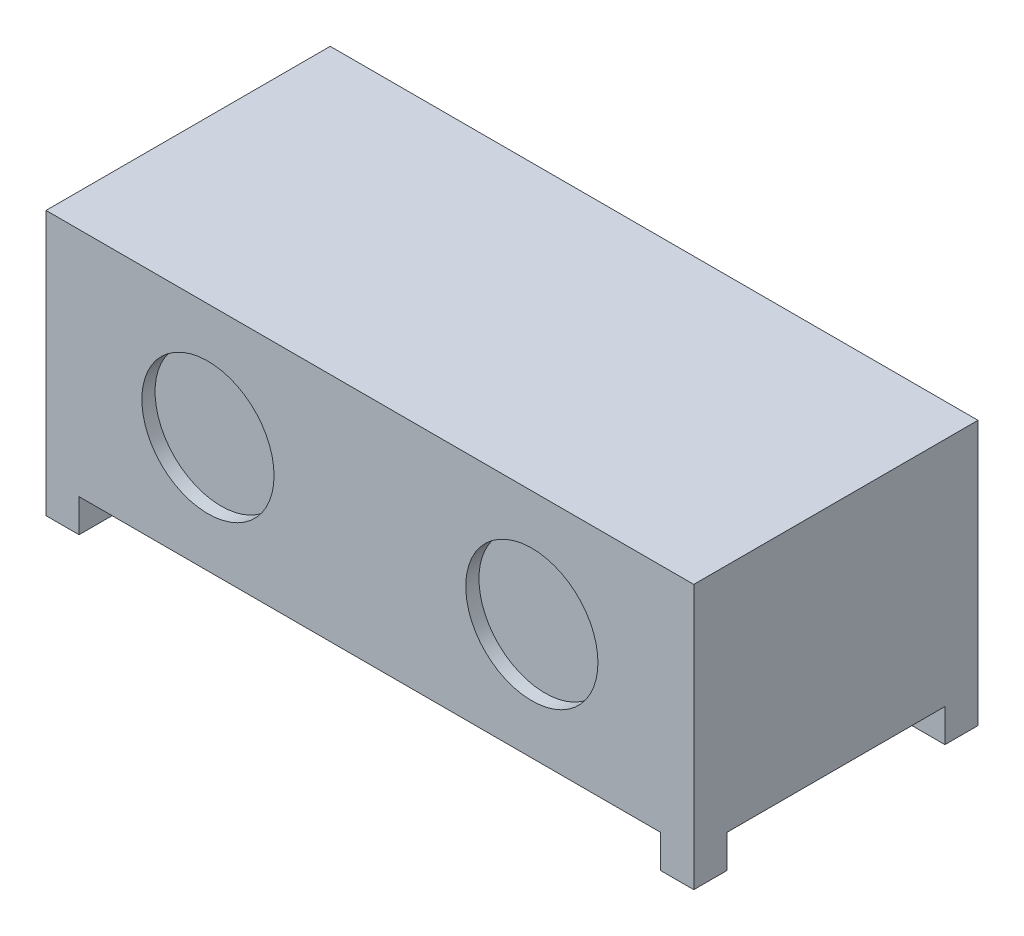
SolidWorks part; units mm, degrees
ref_plane "Front" through (0, 0, 0) normal (0, 0, 1) x (1, 0, 0)
ref_plane "Top" through (0, 0, 0) normal (0, 1, 0) x (1, 0, 0)
ref_plane "Right" through (0, 0, 0) normal (1, 0, 0) x (0, 0, -1)
sketch "Sketch1" plane through (0, 0, 0) normal (0, 1, 0) x (1, 0, 0)
  line L1 (-1244.6, 546.1) -> (1244.6, 546.1)
  line L2 (-1244.6, 546.1) -> (-1244.6, -546.1)
  line L3 (-1244.6, -546.1) -> (1244.6, -546.1)
  line L4 (1244.6, 546.1) -> (1244.6, -546.1)
  line L5 (-1244.6, 546.1) -> (1244.6, -546.1) construction
  line L6 (-1244.6, -546.1) -> (1244.6, 546.1) construction
  point P0 (0, 0)
  dimension "D1" = 2489.2
  dimension "D2" = 1092.2
extrude "Boss-Extrude1" add sketch "Sketch1" along normal blind 889
sketch "Sketch2" plane through (0, 0, 546.1) normal (0, 0, 1) x (1, 0, 0)
  line L0 (0, 0) -> (0, 889) construction
  line L1 (-1244.6, 0) -> (1244.6, 0) construction
  line L2 (-1244.6, 889) -> (1244.6, 889) construction
  line L3 (0, 444.5) -> (-1244.6, 444.5) construction
  line L4 (-1244.6, 889) -> (-1244.6, 0) construction
  line L5 (0, 444.5) -> (1244.6, 444.5) construction
  line L6 (1244.6, 889) -> (1244.6, 0) construction
  circle A0 centre (622.3, 444.5) radius 254
  circle A1 centre (-622.3, 444.5) radius 254
  dimension "D1" = 508
extrude "Cut-Extrude1" cut sketch "Sketch2" against normal blind 50.8
sketch "Sketch3" plane through (0, 0, 0) normal (0, -1, 0) x (1, 0, 0)
  line L1 (-1244.6, 546.1) -> (-1117.6, 546.1)
  line L2 (-1244.6, 546.1) -> (-1244.6, 419.1)
  line L3 (-1244.6, 419.1) -> (-1117.6, 419.1)
  line L4 (-1117.6, 546.1) -> (-1117.6, 419.1)
  line L5 (-1244.6, -546.1) -> (-1117.6, -546.1)
  line L6 (-1244.6, -546.1) -> (-1244.6, -419.1)
  line L7 (-1244.6, -419.1) -> (-1117.6, -419.1)
  line L8 (-1117.6, -546.1) -> (-1117.6, -419.1)
  line L9 (1244.6, 546.1) -> (1117.6, 546.1)
  line L10 (1244.6, 546.1) -> (1244.6, 419.1)
  line L11 (1244.6, 419.1) -> (1117.6, 419.1)
  line L12 (1117.6, 546.1) -> (1117.6, 419.1)
  line L13 (1244.6, -546.1) -> (1117.6, -546.1)
  line L14 (1244.6, -546.1) -> (1244.6, -419.1)
  line L15 (1244.6, -419.1) -> (1117.6, -419.1)
  line L16 (1117.6, -546.1) -> (1117.6, -419.1)
  dimension "D1" = 127
extrude "Boss-Extrude2" add sketch "Sketch3" along normal blind 127
